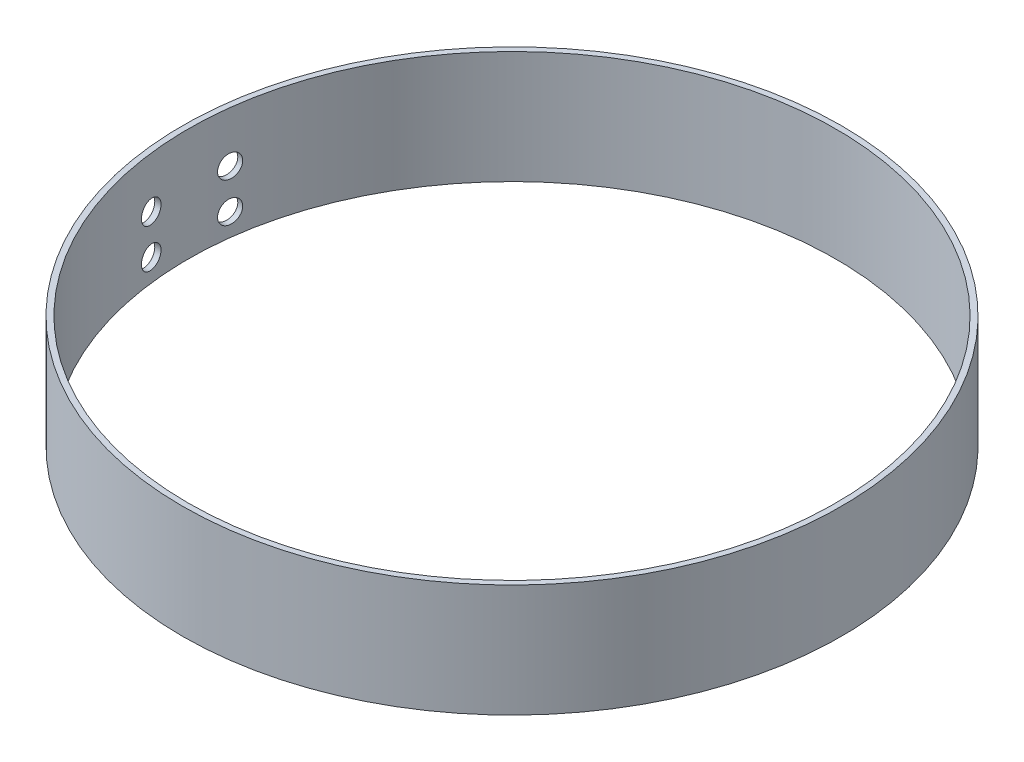
SolidWorks part; units mm, degrees
material "PVC 僵硬"
ref_plane "前视基准面" through (0, 0, 0) normal (0, 0, 1) x (1, 0, 0)
ref_plane "上视基准面" through (0, 0, 0) normal (0, 1, 0) x (1, 0, 0)
ref_plane "右视基准面" through (0, 0, 0) normal (1, 0, 0) x (0, 0, -1)
sketch "草图1" plane through (0, 0, 0) normal (0, 1, 0) x (1, 0, 0)
  circle A0 centre (0, 0) radius 57.5
  circle A1 centre (0, 0) radius 58.5
  dimension "D1" = 115
  dimension "D2" = 1
extrude "凸台-拉伸1" add sketch "草图1" along normal blind 20
sketch3d "3D草图1" plane through (0, 0, 0) normal (0, 0, 1) x (1, 0, 0)
sketch3d "3D草图2" plane through (0, 0, 0) normal (0, 0, 1) x (1, 0, 0)
sketch3d "3D草图3" plane through (0, 0, 0) normal (0, 0, 1) x (1, 0, 0)
  dimension "D1" = 7
sketch3d "3D草图4" plane through (0, 0, 0) normal (0, 0, 1) x (1, 0, 0)
  dimension "D1" = 7
sketch3d "3D草图5" plane through (0, 0, 0) normal (0, 0, 1) x (1, 0, 0)
  dimension "D1" = 90
sketch "草图3" plane through (0, 0, 0) normal (0.9925, 0, -0.1219) x (-0.1219, 0, -0.9925)
  line L1 (-58.5, 0) -> (58.5, 0) construction
  line L2 (0, 50) -> (0, -50) construction
  circle A0 centre (0, 11) radius 2
  circle A1 centre (0, 4) radius 2
  dimension "D1" = 4
  dimension "D2" = 4
  dimension "D3" = 7
  dimension "D4" = 4
extrude "切除-拉伸1" cut sketch "草图3" against normal blind 71
sketch3d "3D草图6" plane through (0, 0, 0) normal (0, 0, 1) x (1, 0, 0)
  dimension "D1" = 90
sketch "草图4" plane through (0, 0, 0) normal (0.9925, 0, 0.1219) x (0.1219, 0, -0.9925)
  line L1 (-58.5, 0) -> (58.5, 0) construction
  line L2 (0, 50) -> (0, -50) construction
  circle A0 centre (0, 11) radius 2
  circle A1 centre (0, 4) radius 2
  dimension "D1" = 4
  dimension "D2" = 4
  dimension "D3" = 7
  dimension "D4" = 4
extrude "切除-拉伸2" cut sketch "草图4" against normal blind 71
